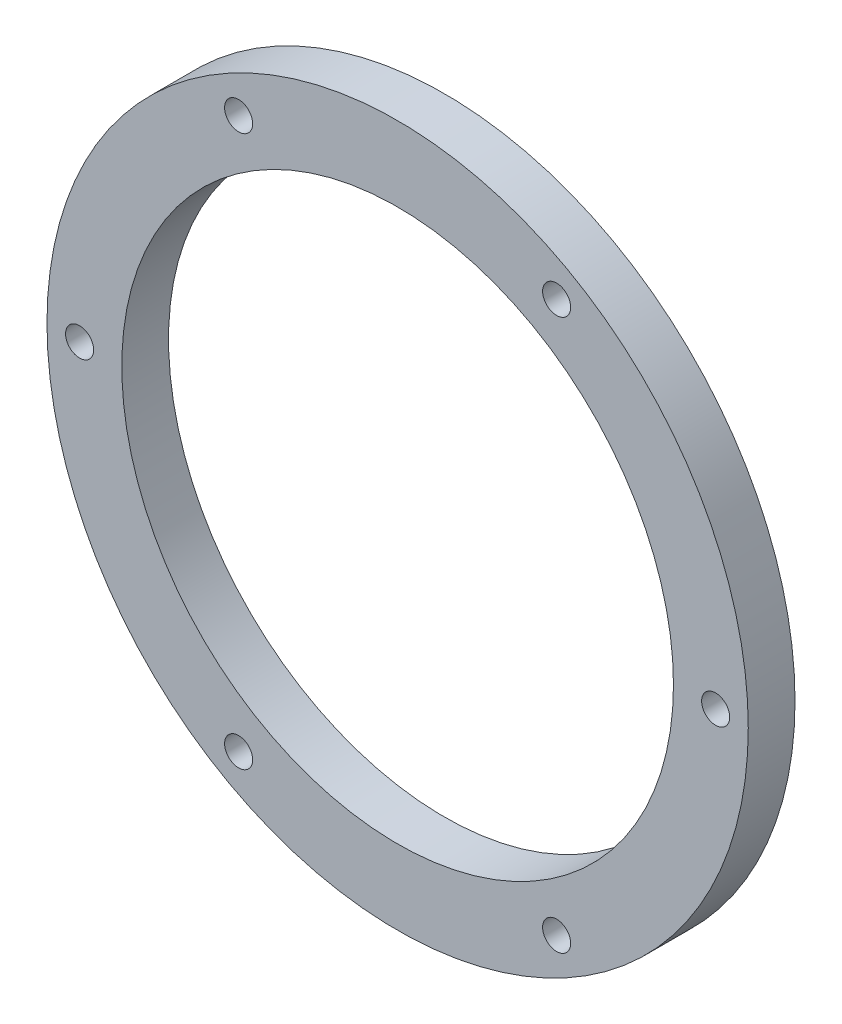
SolidWorks part; units mm, degrees
material "Acrylic (Medium-high impact)"
ref_plane "Front Plane" through (0, 0, 0) normal (0, 0, 1) x (1, 0, 0)
ref_plane "Top Plane" through (0, 0, 0) normal (0, 1, 0) x (1, 0, 0)
ref_plane "Right Plane" through (0, 0, 0) normal (1, 0, 0) x (0, 0, -1)
sketch "Sketch1" plane through (0, 0, 0) normal (0, 0, 1) x (1, 0, 0)
  circle A0 centre (0, 0) radius 37.5
  circle A1 centre (0, 0) radius 29.5
extrude "Boss-Extrude1" add sketch "Sketch1" along normal blind 5
sketch "Sketch2" plane through (0, 0, 0) normal (0, 0, -1) x (-1, 0, 0)
  line L0 (-73.7646, 0) -> (58.2851, 0) construction
  line L1 (27.966, 48.4385) -> (0, 0) construction
  line L2 (0, 0) -> (-33.8549, -58.6384) construction
  line L3 (0, 0) -> (-31.6308, 54.7862) construction
  line L4 (-31.6308, 54.7862) -> (37.1164, -64.2875) construction
  circle A0 centre (0, 0) radius 34.01 construction
  circle A1 centre (-17.005, 29.4535) radius 1.5
  circle A2 centre (0, 0) radius 32.5 construction
  circle A3 centre (17.005, 29.4535) radius 1.5
  circle A4 centre (34.01, 0) radius 1.5
  circle A5 centre (17.005, -29.4535) radius 1.5
  circle A6 centre (-17.005, -29.4535) radius 1.5
  circle A7 centre (-34.01, 0) radius 1.5
  dimension "D1" = 60
  dimension "D2" = 60
extrude "Cut-Extrude1" cut sketch "Sketch2" against normal blind 11
